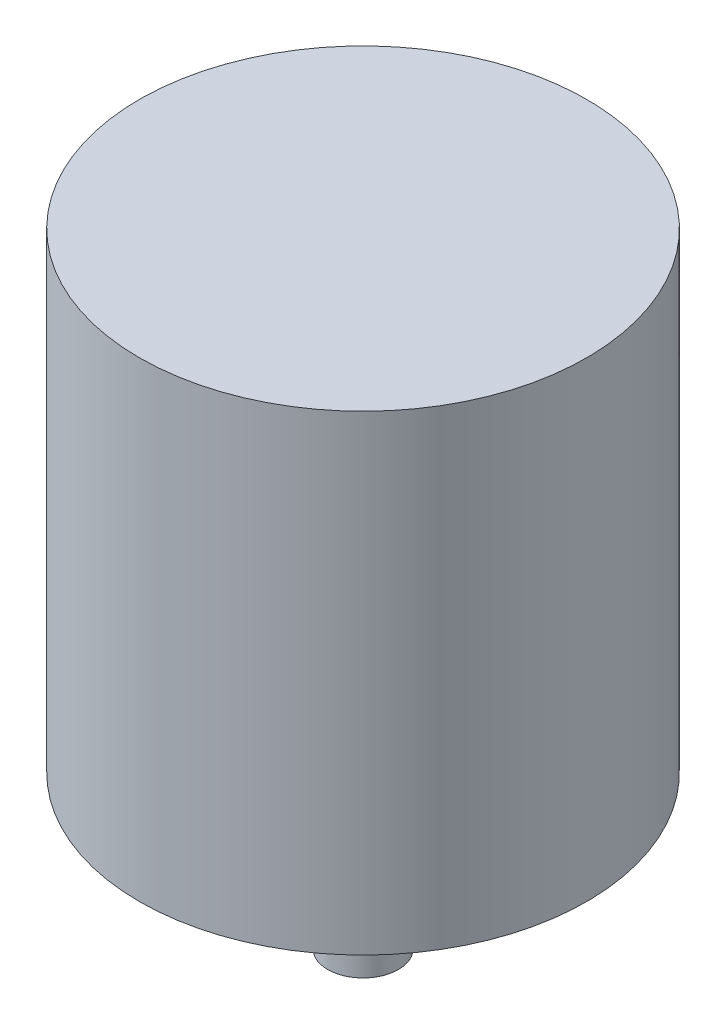
SolidWorks part; units mm, degrees
ref_plane "Front Plane" through (0, 0, 0) normal (0, 0, 1) x (1, 0, 0)
ref_plane "Top Plane" through (0, 0, 0) normal (0, 1, 0) x (1, 0, 0)
ref_plane "Right Plane" through (0, 0, 0) normal (1, 0, 0) x (0, 0, -1)
sketch "Sketch1" plane through (0, 0, 0) normal (0, 1, 0) x (1, 0, 0)
  circle A0 centre (0, 0) radius 19
extrude "Boss-Extrude1" add sketch "Sketch1" along normal blind 40 contours A0
sketch "Sketch2" plane through (0, 0, 0) normal (0, -1, 0) x (1, 0, 0)
  circle A0 centre (0, 0) radius 3
extrude "Boss-Extrude2" add sketch "Sketch2" along normal blind 13
